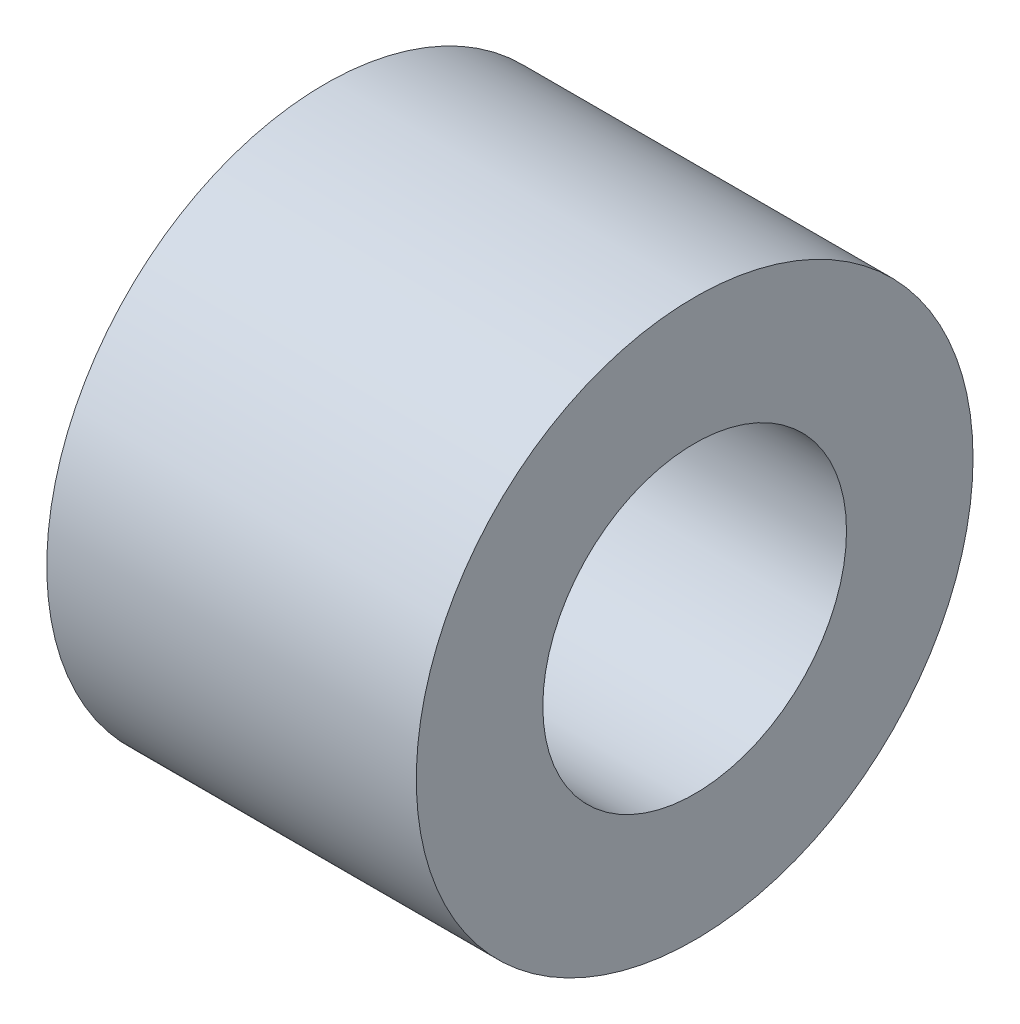
SolidWorks part; units mm, degrees
ref_plane "前视基准面" through (0, 0, 0) normal (0, 0, 1) x (1, 0, 0)
ref_plane "上视基准面" through (0, 0, 0) normal (0, 1, 0) x (1, 0, 0)
ref_plane "右视基准面" through (0, 0, 0) normal (1, 0, 0) x (0, 0, -1)
sketch "草图2" plane through (0, 0, 0) normal (1, 0, 0) x (0, 0, -1)
  circle A0 centre (0, 0) radius 3
  circle A1 centre (0, 0) radius 5.5
extrude "凸台-拉伸1" add sketch "草图2" along normal blind 7.3
